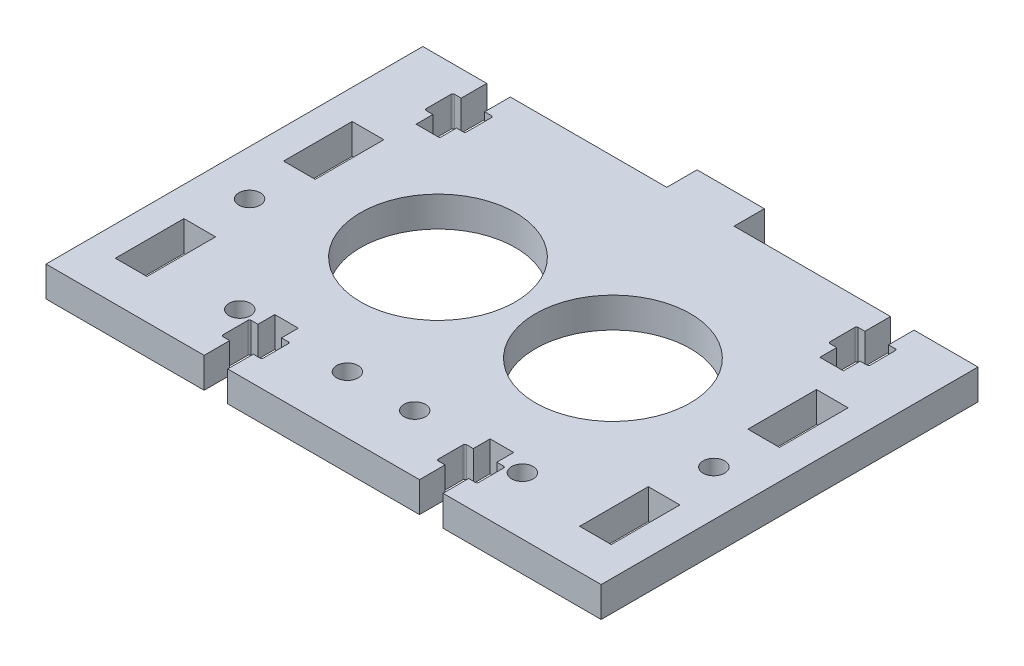
SolidWorks part; units mm, degrees
ref_plane "Front Plane" through (0, 0, 0) normal (0, 0, 1) x (1, 0, 0)
ref_plane "Top Plane" through (0, 0, 0) normal (0, 1, 0) x (1, 0, 0)
ref_plane "Right Plane" through (0, 0, 0) normal (1, 0, 0) x (0, 0, -1)
sketch "Sketch1" plane through (0, 0, 0) normal (0, 1, 0) x (1, 0, 0)
  line L1 (-41.25, 28) -> (41.25, 28)
  line L2 (-41.25, 28) -> (-41.25, -28)
  line L3 (-41.25, -28) -> (41.25, -28)
  line L4 (41.25, 28) -> (41.25, -28)
  line L5 (-41.25, 28) -> (41.25, -28) construction
  line L6 (-41.25, -28) -> (41.25, 28) construction
  point P0 (0, 0)
  dimension "D1" = 82.5
  dimension "D2" = 56
extrude "MainShape" add sketch "Sketch1" along normal blind 4.5
sketch "Sketch2" plane through (0, 4.5, 0) normal (0, 1, 0) x (1, 0, 0)
  line L0 (0, -28) -> (0, 28) construction
  line L1 (-41.25, -28) -> (41.25, -28) construction
  line L2 (41.25, 28) -> (-41.25, 28) construction
  line L4 (-5, 32.5) -> (5, 32.5)
  line L5 (-5, 32.5) -> (-5, 23.5)
  line L6 (-5, 23.5) -> (5, 23.5)
  line L7 (5, 32.5) -> (5, 23.5)
  line L8 (-5, 32.5) -> (5, 23.5) construction
  line L9 (-5, 23.5) -> (5, 32.5) construction
  dimension "D1" = 10
  dimension "D2" = 4.5
extrude "Tab1" add sketch "Sketch2" against normal through all
sketch "Sketch4" plane through (0, 4.5, 0) normal (0, 1, 0) x (1, 0, 0)
  line L0 (0, 32.5) -> (0, -28) construction
  line L1 (5, 32.5) -> (-5, 32.5) construction
  line L2 (-41.25, -28) -> (41.25, -28) construction
  line L3 (-30, 28) -> (-30, 17.5) construction
  line L4 (-5, 28) -> (-41.25, 28) construction
  line L5 (-28.25, 17.5) -> (-31.75, 17.5) construction
  line L6 (-31.75, 17.5) -> (-31.75, 28) construction
  line L7 (-28.25, 17.5) -> (-31.75, 17.5)
  line L8 (-31.75, 17.5) -> (-31.75, 20)
  line L9 (-31.75, 20) -> (-32.75, 20)
  line L10 (-33, 20.25) -> (-33, 23.95)
  line L11 (-32.75, 24.2) -> (-31.75, 24.2)
  line L12 (-31.75, 24.2) -> (-31.75, 28)
  line L13 (-31.75, 28) -> (-28.25, 28)
  line L14 (-28.25, 17.5) -> (-28.25, 28) construction
  line L15 (-28.25, 24.2) -> (-28.25, 28)
  line L16 (-27.25, 24.2) -> (-28.25, 24.2)
  line L17 (-27, 20.25) -> (-27, 23.95)
  line L18 (-28.25, 20) -> (-27.25, 20)
  line L19 (-28.25, 17.5) -> (-28.25, 20)
  line L20 (28.25, 17.5) -> (28.25, 28) construction
  line L21 (31.75, 17.5) -> (31.75, 28) construction
  line L22 (28.25, 17.5) -> (31.75, 17.5) construction
  line L23 (30, 28) -> (30, 17.5) construction
  line L24 (28.25, 17.5) -> (28.25, 20)
  line L25 (28.25, 20) -> (27.25, 20)
  line L26 (27, 20.25) -> (27, 23.95)
  line L27 (27.25, 24.2) -> (28.25, 24.2)
  line L28 (28.25, 24.2) -> (28.25, 28)
  line L29 (31.75, 28) -> (28.25, 28)
  line L30 (31.75, 24.2) -> (31.75, 28)
  line L31 (32.75, 24.2) -> (31.75, 24.2)
  line L32 (33, 20.25) -> (33, 23.95)
  line L33 (31.75, 20) -> (32.75, 20)
  line L34 (31.75, 17.5) -> (31.75, 20)
  line L35 (28.25, 17.5) -> (31.75, 17.5)
  arc A0 (-32.75, 20) -> (-33, 20.25) centre (-32.75, 20.25) cw
  arc A1 (-27, 20.25) -> (-27.25, 20) centre (-27.25, 20.25) cw
  arc A2 (-27.25, 24.2) -> (-27, 23.95) centre (-27.25, 23.95) cw
  arc A3 (-33, 23.95) -> (-32.75, 24.2) centre (-32.75, 23.95) cw
  arc A4 (33, 23.95) -> (32.75, 24.2) centre (32.75, 23.95) ccw
  arc A5 (27.25, 24.2) -> (27, 23.95) centre (27.25, 23.95) ccw
  arc A6 (27, 20.25) -> (27.25, 20) centre (27.25, 20.25) ccw
  arc A7 (32.75, 20) -> (33, 20.25) centre (32.75, 20.25) ccw
  point P24 (-33, 20)
  point P27 (-27, 20)
  point P30 (-27, 24.2)
  point P33 (-33, 24.2)
  point P56 (33, 24.2)
  point P57 (27, 24.2)
  point P58 (27, 20)
  point P59 (33, 20)
  dimension "D7" = 0.25
  dimension "D1" = 10.5
  dimension "D2" = 1.75
  dimension "D3" = 4.2
  dimension "D4" = 3
  dimension "D5" = 8
  dimension "D6" = 30
extrude "Cut-Extrude2" cut sketch "Sketch4" against normal through all
sketch "Sketch5" plane through (0, 4.5, 0) normal (0, 1, 0) x (1, 0, 0)
  line L0 (0, -28) -> (0, 32.5) construction
  line L1 (-41.25, -28) -> (41.25, -28) construction
  line L2 (5, 32.5) -> (-5, 32.5) construction
  line L3 (34.5, 28) -> (34.5, -28) construction
  line L4 (41.25, 28) -> (31.75, 28) construction
  line L5 (-34.5, 28) -> (-34.5, -28) construction
  line L6 (32.15, 13.1) -> (36.85, 13.1)
  line L7 (32.15, 13.1) -> (32.15, 2.9)
  line L8 (32.15, 2.9) -> (36.85, 2.9)
  line L9 (36.85, 13.1) -> (36.85, 2.9)
  line L10 (32.15, 13.1) -> (36.85, 2.9) construction
  line L11 (32.15, 2.9) -> (36.85, 13.1) construction
  line L12 (-32.15, 2.9) -> (-36.85, 13.1) construction
  line L13 (-32.15, 13.1) -> (-36.85, 2.9) construction
  line L14 (-36.85, 13.1) -> (-36.85, 2.9)
  line L15 (-32.15, 2.9) -> (-36.85, 2.9)
  line L16 (-32.15, 13.1) -> (-32.15, 2.9)
  line L17 (-32.15, 13.1) -> (-36.85, 13.1)
  line L18 (-41.25, -4.5) -> (41.25, -4.5) construction
  line L19 (-41.25, 28) -> (-41.25, -28) construction
  line L20 (41.25, -28) -> (41.25, 28) construction
  line L21 (-32.15, -22.1) -> (-36.85, -11.9) construction
  line L22 (-32.15, -11.9) -> (-36.85, -22.1) construction
  line L23 (32.15, -11.9) -> (36.85, -22.1) construction
  line L24 (32.15, -22.1) -> (36.85, -11.9) construction
  line L25 (-32.15, -22.1) -> (-36.85, -22.1)
  line L26 (-32.15, -22.1) -> (-32.15, -11.9)
  line L27 (-32.15, -11.9) -> (-36.85, -11.9)
  line L28 (-36.85, -22.1) -> (-36.85, -11.9)
  line L29 (36.85, -22.1) -> (36.85, -11.9)
  line L30 (32.15, -11.9) -> (36.85, -11.9)
  line L31 (32.15, -22.1) -> (32.15, -11.9)
  line L32 (32.15, -22.1) -> (36.85, -22.1)
  line L33 (-32.15, 13.1) -> (-36.85, 2.9) construction
  circle A0 centre (34.5, -4.5) radius 1.6
  circle A1 centre (-34.5, -4.5) radius 1.6
  point P10 (34.5, 8)
  point P21 (-34.5, 8)
  point P36 (-34.5, -17)
  point P37 (34.5, -17)
  dimension "D6" = 3.2
  dimension "D1" = 34.5
  dimension "D2" = 10.2
  dimension "D3" = 4.7
  dimension "D4" = 20
  dimension "D5" = 25
extrude "Cut-Extrude3" cut sketch "Sketch5" against normal through all
sketch "Sketch6" plane through (0, 4.5, 0) normal (0, 1, 0) x (1, 0, 0)
  line L0 (-13, -28) -> (-13, 28) construction
  line L2 (5, 32.5) -> (-5, 32.5) construction
  line L3 (-41.25, 2) -> (41.25, 2) construction
  line L4 (-41.25, 28) -> (-41.25, -28) construction
  line L5 (41.25, -28) -> (41.25, 28) construction
  line L6 (41.25, 28) -> (31.75, 28) construction
  line L7 (-41.25, -28) -> (41.25, -28) construction
  line L9 (-41.25, 28) -> (41.25, 28) construction
  circle A0 centre (-13, 2) radius 11.5
  point P4 (0, 32.5)
  dimension "D1" = 23
  dimension "D2" = 26
  dimension "D4" = 13
extrude "Cut-Extrude4" cut sketch "Sketch6" against normal through all
sketch "Sketch8" plane through (0, 4.5, 0) normal (0, 1, 0) x (1, 0, 0)
  line L0 (-24.5, 2) -> (-1.5, 2) construction
  line L1 (-13, 2) -> (-13, -19.46) construction
  line L2 (-5, -19.46) -> (-21, -19.46) construction
  line L3 (-13, -9.5) -> (-13, 13.5) construction
  circle A0 centre (-21, -19.46) radius 1.6
  circle A1 centre (-13, 2) radius 11.5 construction
  circle A2 centre (-5, -19.46) radius 1.6
  dimension "D3" = 3.2
  dimension "D1" = 90
  dimension "D2" = 8
  dimension "D4" = 21.46
extrude "Cut-Extrude6" cut sketch "Sketch8" against normal through all
sketch "Sketch9" plane through (0, 4.5, 0) normal (0, 1, 0) x (1, 0, 0)
  line L0 (0, -28) -> (0, 32.5) construction
  line L1 (-41.25, -28) -> (41.25, -28) construction
  line L2 (5, 32.5) -> (-5, 32.5) construction
  line L3 (16, -28) -> (16, -17.5) construction
  line L4 (14.25, -17.5) -> (17.75, -17.5) construction
  line L5 (17.75, -17.5) -> (17.75, -28) construction
  line L6 (17.75, -28) -> (17.75, -24.2)
  line L7 (17.75, -24.2) -> (18.75, -24.2)
  line L8 (19, -23.95) -> (19, -20.25)
  line L9 (18.75, -20) -> (17.75, -20)
  line L10 (17.75, -20) -> (17.75, -17.5)
  line L11 (17.75, -17.5) -> (14.25, -17.5)
  line L12 (17.75, -28) -> (14.25, -28)
  line L13 (14.25, -17.5) -> (14.25, -28) construction
  line L14 (14.25, -20) -> (14.25, -17.5)
  line L15 (13.25, -20) -> (14.25, -20)
  line L16 (13, -23.95) -> (13, -20.25)
  line L17 (14.25, -24.2) -> (13.25, -24.2)
  line L18 (14.25, -28) -> (14.25, -24.2)
  line L19 (-14.25, -17.5) -> (-14.25, -28) construction
  line L20 (-17.75, -17.5) -> (-17.75, -28) construction
  line L21 (-14.25, -17.5) -> (-17.75, -17.5) construction
  line L22 (-16, -28) -> (-16, -17.5) construction
  line L23 (-14.25, -28) -> (-14.25, -24.2)
  line L24 (-14.25, -24.2) -> (-13.25, -24.2)
  line L25 (-13, -23.95) -> (-13, -20.25)
  line L26 (-13.25, -20) -> (-14.25, -20)
  line L27 (-14.25, -20) -> (-14.25, -17.5)
  line L28 (-17.75, -28) -> (-14.25, -28)
  line L29 (-17.75, -17.5) -> (-14.25, -17.5)
  line L30 (-17.75, -20) -> (-17.75, -17.5)
  line L31 (-18.75, -20) -> (-17.75, -20)
  line L32 (-19, -23.95) -> (-19, -20.25)
  line L33 (-17.75, -24.2) -> (-18.75, -24.2)
  line L34 (-17.75, -28) -> (-17.75, -24.2)
  arc A0 (18.75, -24.2) -> (19, -23.95) centre (18.75, -23.95) ccw
  arc A1 (19, -20.25) -> (18.75, -20) centre (18.75, -20.25) ccw
  arc A2 (13, -20.25) -> (13.25, -20) centre (13.25, -20.25) cw
  arc A3 (13.25, -24.2) -> (13, -23.95) centre (13.25, -23.95) cw
  arc A4 (-13.25, -24.2) -> (-13, -23.95) centre (-13.25, -23.95) ccw
  arc A5 (-13, -20.25) -> (-13.25, -20) centre (-13.25, -20.25) ccw
  arc A6 (-19, -20.25) -> (-18.75, -20) centre (-18.75, -20.25) cw
  arc A7 (-18.75, -24.2) -> (-19, -23.95) centre (-18.75, -23.95) cw
  point P16 (19, -24.2)
  point P19 (19, -20)
  point P30 (13, -20)
  point P31 (13, -24.2)
  point P54 (-13, -24.2)
  point P55 (-13, -20)
  point P56 (-19, -20)
  point P57 (-19, -24.2)
  dimension "D7" = 0.25
  dimension "D1" = 10.5
  dimension "D2" = 1.75
  dimension "D3" = 8
  dimension "D4" = 4.2
  dimension "D5" = 3
  dimension "D6" = 16
extrude "Cut-Extrude7" cut sketch "Sketch9" against normal through all
sketch "Sketch10" [suppressed] plane through (0, 0, 28) normal (0, 0, 1) x (1, 0, 0)
  line L0 (-55, 2.25) -> (55, 2.25) construction
  line L1 (-55, 4.5) -> (-55, 0) construction
  line L2 (55, 4.5) -> (55, 0) construction
  line L3 (-16, 4.5) -> (-16, 0) construction
  line L4 (-14.25, 4.5) -> (-17.75, 4.5) construction
  line L5 (16, 4.5) -> (16, 0) construction
  line L6 (17.75, 4.5) -> (14.25, 4.5) construction
  line L7 (17.75, 0) -> (14.25, 0) construction
  line L8 (-14.25, 0) -> (-17.75, 0) construction
  circle A0 centre (-16, 2.25) radius 1.6
  circle A1 centre (16, 2.25) radius 1.6
  dimension "D1" = 3.2
  dimension "D2" = 3.2
mirror "Mirror1" about plane through (0, 0, 0) normal (1, 0, 0) of "Cut-Extrude6", "Cut-Extrude4"
equation "\"X-ROD-SPACING\"=45"
equation "\"Y-ROD-SPACING\"=75"
equation "\"Z-ROD-SPACING\"=17.5"
equation "\"Y-BED-OFFSET\"=2"
equation "\"Y-BED-ROD-INSET\"=3.5"
equation "\"Y-BED-SCREW-SPACING\"=209"
equation "\"Y-BED-SCREW-CUTOUT-SLOT-HEIGHT\"=1"
equation "\"T-SLOT-NUT-FILLET-RADIUS\"=0.25"
equation "\"T-SLOT-SCREW-SHAFT-RADIUS\"=1.75"
equation "\"T-SLOT-SCREW-SHAFT-CUTOUT-LENGTH\"=10.5"
equation "\"T-SLOT-NUT-DEPTH\"=4.2"
equation "\"T-SLOT-NUT-WIDTH\"=3"
equation "\"T-SLOT-NUT-END-DISTANCE\"=8"
equation "\"ACRYLIC-THICKNESS\"=10"
equation "\"ACRYLIC-THICKNESS2\"=4.5"
equation "\"ACRYLIC-TAB-CUTOUT-SIZE\"=\"ACRYLIC-THICKNESS\"+\"ACRYLIC-TAB-TOLERANCE\"*2"
equation "\"ACRYLIC-TAB-WIDTH\"=\"ACRYLIC-THICKNESS\""
equation "\"ACRYLIC-M3-HOLE\"=3.2"
equation "\"SMOOTHROD-CAP-SCREW-DISTANCE\"=20"
equation "\"FRAME-WIDTH-INNER\"=370"
equation "\"NEMA17-HOLE-SPACING\"=31"
equation "\"NEMA17-CENTRAL-CUTOUT\"=22.5"
equation "\"Z-BRACKET-REACH\"=55"
equation "\"Z-ROD-INSET\"=16"
equation "\"TOP-BRACKET-SPACING\"=40"
equation "\"SMOOTHROD-X-LENGTH\"=350"
equation "\"SMOOTHROD-Y-LENGTH\"=350"
equation "\"SMOOTHROD-Z-LENGTH\"=350"
equation "\"SMOOTHROD-TIGHTENING-HEADROOM\"=1"
equation "\"LEADSCREW-Z-LENGTH\"=300"
equation "\"SCREW-LENGTH-FRAME\"=\"ACRYLIC-THICKNESS\" + 10"
equation "\"SCREW-LENGTH-MOTOR\"=\"ACRYLIC-THICKNESS\" + 5"
equation "\"SCREW-LENGTH-EXTRUDER\"=28"
equation "\"SCREW-HEAD-RADIUS\"=6"
equation "\"PRINTED-X-SMOOTHROD-DIAMETER\"=8.2"
equation "\"PRINTED-X-SMOOTHROD-CUTOUT\"=10"
equation "\"PRINTED-X-BASE-HEIGHT\"=10"
equation "\"PRINTED-LM8UU-CUTOUT-SIZE\"=16"
equation "\"PRINTED-LM8UU-CUTOUT-LENGTH\"=24.5"
equation "\"PRINTED-X-IDLER-HEIGHT\"=16"
equation "\"PSU-MOUNTING-WIDTH\"=95"
equation "\"PSU-MOUNTING-HEIGHT\"=177"
equation "\"Y-BELT-TO-ROD-DISTANCE\"=20"
equation "\"SPOOL-HOLDER-ROD-SPACING\"=150"
equation "\"ACRYLIC-X-CARRIAGE-WIDTH\"=55"
equation "\"ACRYLIC-X-CARRIAGE-HEIGHT\"=75"
equation "\"ACRYLIC-X-CARRIAGE-SCREW-SPACING-X\"=15"
equation "\"ACRYLIC-X-CARRIAGE-SCREW-SPACING-Y\"=33"
equation "\"ACRYLIC-X-CARRIAGE-CENTER-TAB-SPACING\"=14"
equation "\"D1@Sketch1\"=\"ACRYLIC-X-CARRIAGE-WIDTH\"*1.5"
equation "\"D1@MainShape\" = \"ACRYLIC-THICKNESS2\""
equation "\"D1@Sketch2\"=\"ACRYLIC-TAB-WIDTH\""
equation "\"D2@Sketch2\"=\"ACRYLIC-THICKNESS2\""
equation "\"D1@Sketch4\"=\"T-SLOT-SCREW-SHAFT-CUTOUT-LENGTH\""
equation "\"D2@Sketch4\"=\"T-SLOT-SCREW-SHAFT-RADIUS\""
equation "\"D3@Sketch4\"=\"T-SLOT-NUT-DEPTH\""
equation "\"D4@Sketch4\"=\"T-SLOT-NUT-WIDTH\""
equation "\"D5@Sketch4\"=\"T-SLOT-NUT-END-DISTANCE\""
equation "\"D6@Sketch4\"=\"ACRYLIC-X-CARRIAGE-SCREW-SPACING-X\"*2"
equation "\"D7@Sketch4\"=\"T-SLOT-NUT-FILLET-RADIUS\""
equation "\"ACRYLIC-X-CARRIAGE-EXTRUDER-SHELF-DEPTH\"=\"ACRYLIC-X-CARRIAGE-EXTRUDER-OFFSET\" + 30"
equation "\"D2@Sketch1\"=\"ACRYLIC-X-CARRIAGE-EXTRUDER-SHELF-DEPTH\""
equation "\"ACRYLIC-X-CARRIAGE-LM8UU-CUTOUT-WIDTH\"=24.25"
equation "\"ACRYLIC-X-CARRIAGE-EXTRUDER-BRACE-SPACING\"=23"
equation "\"ACRYLIC-X-CARRIAGE-EXTRUDER-BRACE-TAB-OFFSET\"=20"
equation "\"ACRYLIC-X-CARRIAGE-EXTRUDER-BRACE-HEIGHT\"=35"
equation "\"ACRYLIC-X-CARRIAGE-EXTRUDER-BRACE-SCREW-SPACING\"=22"
equation "\"D1@Sketch5\"=\"ACRYLIC-X-CARRIAGE-EXTRUDER-BRACE-SPACING\"*1.5"
equation "\"D2@Sketch5\"=\"ACRYLIC-TAB-CUTOUT-SIZE\""
equation "\"D3@Sketch5\"=\"ACRYLIC-THICKNESS2\"+\"ACRYLIC-TAB-TOLERANCE\"*2"
equation "\"D4@Sketch5\"=\"ACRYLIC-X-CARRIAGE-EXTRUDER-BRACE-TAB-OFFSET\""
equation "\"D3@Sketch8\"=\"ACRYLIC-M3-HOLE\""
equation "\"ACRYLIC-X-CARRIAGE-EXTRUDER-ANGLE\"=90"
equation "\"D1@Sketch8\"=\"ACRYLIC-X-CARRIAGE-EXTRUDER-ANGLE\""
equation "\"ACRYLIC-X-CARRIAGE-EXTRUDER-OFFSET\"=26"
equation "\"D2@Sketch6\"=\"ACRYLIC-X-CARRIAGE-EXTRUDER-OFFSET\""
equation "\"D6@Sketch5\"=\"ACRYLIC-M3-HOLE\""
equation "\"D1@Sketch9\"=\"T-SLOT-SCREW-SHAFT-CUTOUT-LENGTH\""
equation "\"D2@Sketch9\"=\"T-SLOT-SCREW-SHAFT-RADIUS\""
equation "\"D3@Sketch9\"=\"T-SLOT-NUT-END-DISTANCE\""
equation "\"D4@Sketch9\"=\"T-SLOT-NUT-DEPTH\""
equation "\"D5@Sketch9\"=\"T-SLOT-NUT-WIDTH\""
equation "\"D7@Sketch9\"=\"T-SLOT-NUT-FILLET-RADIUS\""
equation "\"ACRYLIC-TAB-TOLERANCE\"=.1"
